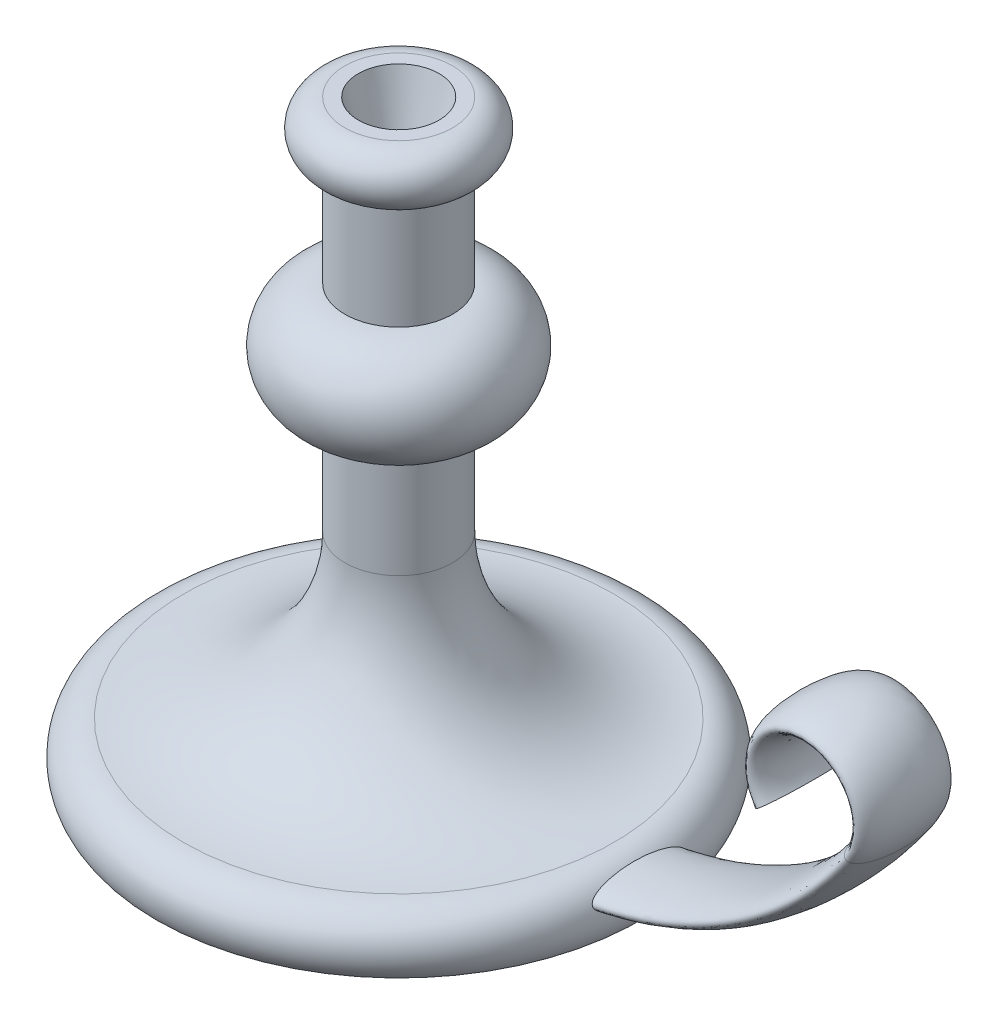
SolidWorks part; units mm, degrees
ref_plane "Front Plane" through (0, 0, 0) normal (0, 0, 1) x (1, 0, 0)
ref_plane "Top Plane" through (0, 0, 0) normal (0, 1, 0) x (1, 0, 0)
ref_plane "Right Plane" through (0, 0, 0) normal (1, 0, 0) x (0, 0, -1)
sketch "Sketch1" plane through (0, 0, 0) normal (0, 0, 1) x (1, 0, 0)
  line L0 (0, 0) -> (0, 220)
  line L1 (0, 220) -> (20, 220)
  line L2 (0, 0) -> (90, 0)
  line L3 (20, 200) -> (20, 160)
  line L4 (20, 120) -> (20, 80)
  arc A0 (20, 220) -> (20, 200) centre (20, 210) cw
  arc A1 (20, 120) -> (20, 160) centre (20, 140) ccw
  arc A2 (20, 80) -> (80, 20) centre (80, 80) ccw
  arc A3 (80, 20) -> (90, 0) centre (80, 7.5) cw
  dimension "D4" = 10
  dimension "D5" = 20
  dimension "D8" = 60
  dimension "D1" = 220
  dimension "D2" = 20
  dimension "D3" = 90
  dimension "D6" = 40
  dimension "D7" = 40
  dimension "D9" = 90
revolve "Revolve1" add sketch "Sketch1" angle 360 about L0
sketch "Sketch2" plane through (0, 0, 0) normal (0, 0, 1) x (1, 0, 0)
  line L1 (0, 227.4356) -> (0, 175.1288) construction
  line L2 (0, 200) -> (0, 160) construction
  line L3 (0, 10) -> (60, 10)
  line L4 (-90, 0) -> (90, 0) construction
  arc A0 (60, 10) -> (183.5921, 75) centre (60, 160) ccw
  arc A1 (183.5921, 75) -> (150.6342, 75) centre (167.1131, 86.3333) ccw
  dimension "D2" = 150
  dimension "D4" = 20
  dimension "D1" = 60
  dimension "D3" = 65
  dimension "D5" = 10
sketch "Sketch3" plane through (0, 0, 0) normal (1, 0, 0) x (0, 0, -1)
  ellipse E0 centre (0, 10) end of major axis (17.5, 10) minor radius 5
  dimension "D1" = 10
  dimension "D2" = 35
sweep "Sweep3" add profiles "Sketch3" path "Sketch2"
sketch "Sketch7" plane through (0, 220, 0) normal (0, 1, 0) x (1, 0, 0)
  circle A0 centre (0, 0) radius 15
  dimension "D1" = 30
extrude "Cut-Extrude1" cut sketch "Sketch7" against normal blind 25 draft 15
